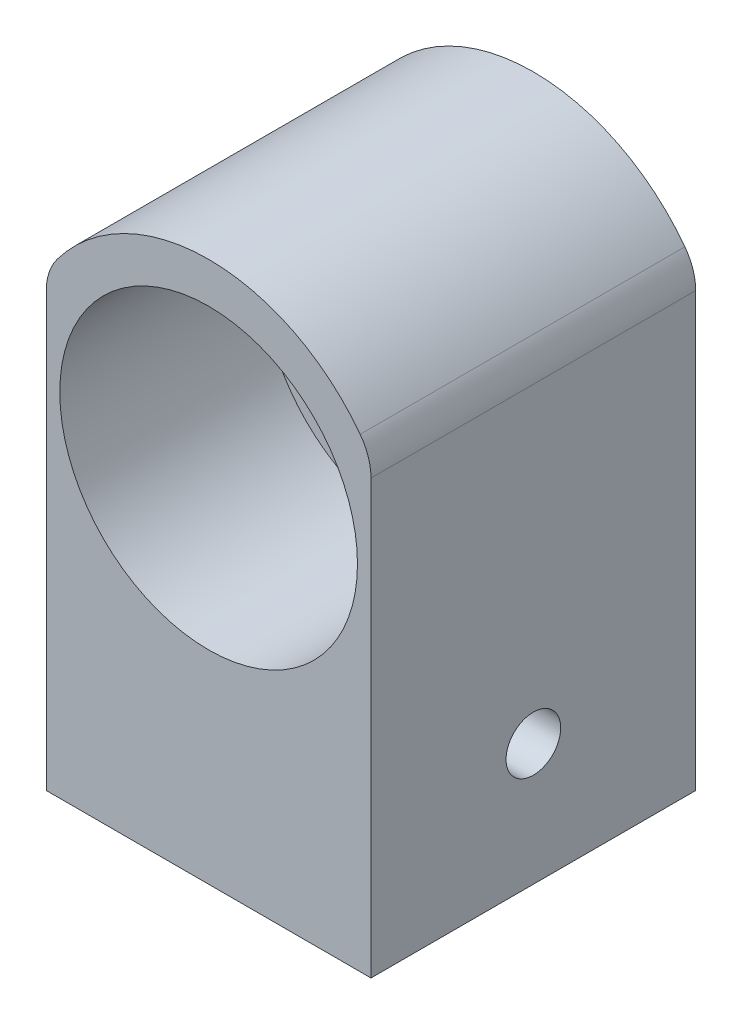
SolidWorks part; units mm, degrees
material "6061-T6 (SS)"
ref_plane "Front" through (0, 0, 0) normal (0, 0, 1) x (1, 0, 0)
ref_plane "Top" through (0, 0, 0) normal (0, 1, 0) x (1, 0, 0)
ref_plane "Right" through (0, 0, 0) normal (1, 0, 0) x (0, 0, -1)
sketch "Sketch1" plane through (0, 0, 0) normal (0, 1, 0) x (1, 0, 0)
  line L1 (-38.1, -38.1) -> (38.1, -38.1)
  line L2 (-38.1, -38.1) -> (-38.1, 38.1)
  line L3 (-38.1, 38.1) -> (38.1, 38.1)
  line L4 (38.1, -38.1) -> (38.1, 38.1)
  line L5 (-38.1, -38.1) -> (38.1, 38.1) construction
  line L6 (-38.1, 38.1) -> (38.1, -38.1) construction
  point P0 (0, 0)
  dimension "D1" = 76.2
extrude "Boss-Extrude1" add sketch "Sketch1" along normal blind 127
sketch "Sketch3" plane through (0, 0, 38.1) normal (0, 0, 1) x (1, 0, 0)
  line L0 (-38.1, 127) -> (38.1, 127) construction
  circle A0 centre (0, 82.55) radius 34.925
  dimension "D1" = 44.45
  dimension "D2" = 69.85
extrude "Cut-Extrude1" cut sketch "Sketch3" against normal blind 47.625
sketch "Sketch5" plane through (0, 0, -38.1) normal (0, 0, -1) x (-1, 0, 0)
  line L0 (-38.1, 0) -> (38.1, 0) construction
  line L1 (22.225, 73.3441) -> (22.225, 91.7559)
  line L2 (22.225, 91.7559) -> (9.2059, 104.775)
  line L3 (9.2059, 104.775) -> (-9.2059, 104.775)
  line L4 (-9.2059, 104.775) -> (-22.225, 91.7559)
  line L5 (-22.225, 91.7559) -> (-22.225, 73.3441)
  line L6 (-22.225, 73.3441) -> (-9.2059, 60.325)
  line L7 (-9.2059, 60.325) -> (9.2059, 60.325)
  line L8 (9.2059, 60.325) -> (22.225, 73.3441)
  circle A2 centre (0, 82.55) radius 22.225 construction
  point P3 (0, 0)
  point P13 (0, 82.55)
  dimension "D1" = 44.45
extrude "Cut-Extrude3" cut sketch "Sketch5" against normal offset from surface (20.6375 mm away) 7.9375 up to face at (34.925, 82.55, -9.525)
sketch "Sketch6" plane through (0, 0, -17.4625) normal (0, 0, -1) x (-1, 0, 0)
  line L0 (-38.1, 0) -> (38.1, 0) construction
  line L1 (-22.225, 91.7559) -> (-22.225, 73.3441) construction
  circle A0 centre (0, 82.55) radius 20.955
  point P4 (0, 0)
  point P7 (-22.225, 82.55)
  dimension "D1" = 41.91
extrude "Cut-Extrude4" cut sketch "Sketch6" against normal up to next
sketch "Sketch7" plane through (0, 0, 38.1) normal (0, 0, 1) x (1, 0, 0)
  line L0 (-38.1, 127) -> (-38.1, 0) construction
  line L1 (38.1, 127) -> (38.1, 0) construction
  line L2 (-38.1, 127) -> (38.1, 127) construction
  line L3 (-38.1, 105.4453) -> (-38.1, 130.8453)
  line L4 (-38.1, 130.8453) -> (38.1, 130.8453)
  line L5 (38.1, 130.8453) -> (38.1, 105.4453)
  arc A0 (-38.1, 105.4453) -> (38.1, 105.4453) centre (0, 82.55) cw
  dimension "D1" = 25.4
extrude "Cut-Extrude5" cut sketch "Sketch7" against normal up to next
fillet "Fillet1" radius 12.7 2 edges at (38.1, 105.4453, 0) (-38.1, 105.4453, 0)
sketch "Sketch8" plane through (38.1, 0, 0) normal (1, 0, 0) x (0, 0, -1)
  line L0 (-38.1, 0) -> (38.1, 0) construction
  circle A0 centre (0, 28.575) radius 6.4135
  dimension "D1" = 12.827
  dimension "D2" = 28.575
extrude "Cut-Extrude6" cut sketch "Sketch8" against normal through all
sketch "Sketch11" plane through (-38.1, 0, 0) normal (-1, 0, 0) x (0, 0, 1)
  line L0 (0, 28.575) -> (23.8125, 28.575) construction
  point P3 (0, 28.575)
  dimension "D1" = 23.8125
hole_wizard "#10 (0.1935) Diameter Hole1" positions "Sketch13" profile "Sketch12" hole size "#10" standard "Ansi Inch"
sketch "Sketch13" plane through (-38.1, 0, 0) normal (-1, 0, 0) x (0, 0, 1)
  point P0 (23.8125, 28.575)
sketch "Sketch12" plane through (-38.1, 28.575, 23.8125) normal (0, 1, 0) x (0, 0, 1)
  line L0 (0, 0) -> (0, 10.7173)
  line L1 (0, 10.7173) -> (1.9844, 9.525)
  line L2 (1.9844, 9.525) -> (1.9844, 0)
  line L5 (1.9844, 0) -> (0, 0)
  line L10 (0, 10.7173) -> (-1.9844, 9.525) construction
  line L11 (0, -6.35) -> (0, 107.95) construction
  dimension "Hole Dia." = 3.9688
  dimension "Hole Depth" = 9.525
  dimension "Drill Angle" = 118
pattern_circular "CirPattern1" count 6 over 360 about axis through (0, 28.575, 0) along (1, 0, 0) of "#10 (0.1935) Diameter Hole1"
